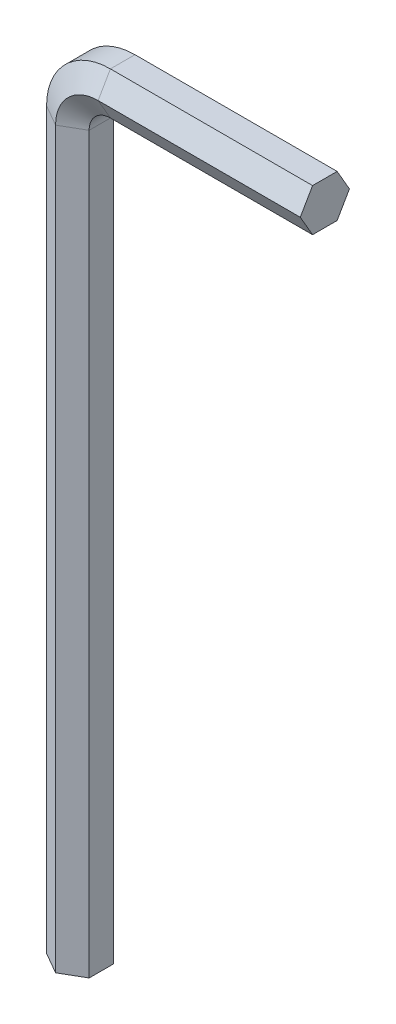
SolidWorks part; units mm, degrees
material "AISI 1020"
ref_plane "Front Plane" through (0, 0, 0) normal (0, 0, 1) x (1, 0, 0)
ref_plane "Top Plane" through (0, 0, 0) normal (0, 1, 0) x (1, 0, 0)
ref_plane "Right Plane" through (0, 0, 0) normal (1, 0, 0) x (0, 0, -1)
sketch "Sketch1" plane through (0, 0, 0) normal (0, 0, 1) x (1, 0, 0)
  line L0 (0, 0) -> (0, 69)
  line L1 (6, 75) -> (25, 75)
  arc A0 (0, 69) -> (6, 75) centre (6, 69) cw
  dimension "D3" = 6
  dimension "D1" = 75
  dimension "D2" = 25
sketch "Sketch2" plane through (0, 0, 0) normal (0, 1, 0) x (1, 0, 0)
  line L0 (4, -1.1547) -> (4, 1.1547)
  line L1 (4, 1.1547) -> (2, 2.3094)
  line L2 (2, 2.3094) -> (0, 1.1547)
  line L3 (0, 1.1547) -> (0, -1.1547)
  line L4 (0, -1.1547) -> (2, -2.3094)
  line L5 (2, -2.3094) -> (4, -1.1547)
  circle A0 centre (2, 0) radius 2.3094 construction
  point P5 (0, 0)
  dimension "D1" = 4
sweep "Sweep1" add profiles "Sketch2" path "Sketch1"
